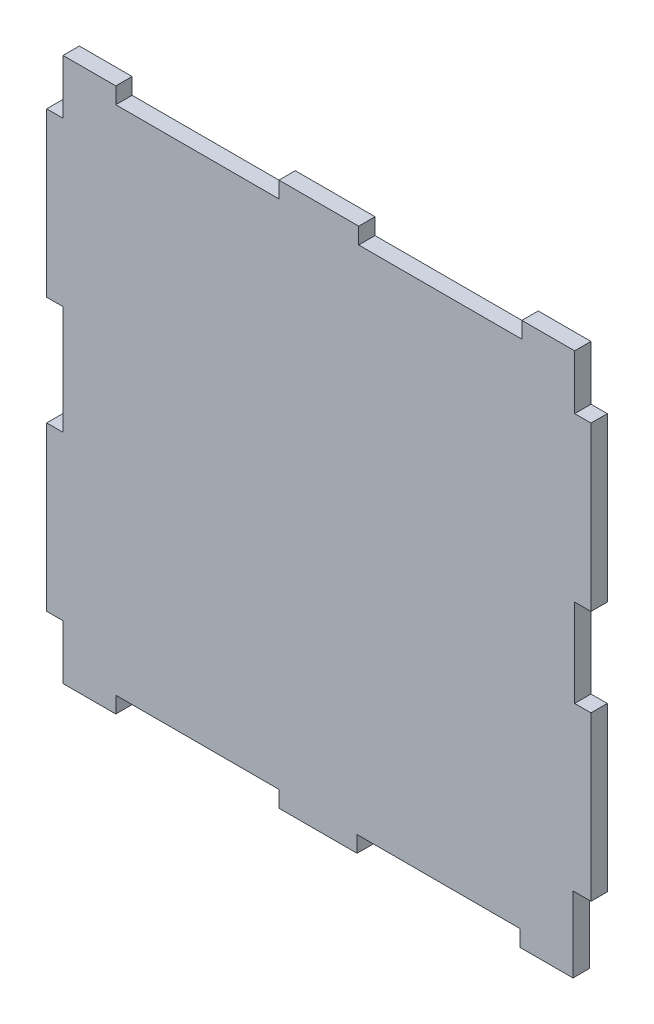
SolidWorks part; units mm, degrees
ref_plane "Plan de face" through (0, 0, 0) normal (0, 0, 1) x (1, 0, 0)
ref_plane "Plan de dessus" through (0, 0, 0) normal (0, 1, 0) x (1, 0, 0)
ref_plane "Plan de droite" through (0, 0, 0) normal (1, 0, 0) x (0, 0, -1)
sketch "Esquisse1" plane through (0, 0, 0) normal (0, 0, 1) x (1, 0, 0)
  line L0 (-57.5181, -33.4139) -> (-57.5181, -63.4139)
  line L1 (-54.5181, 26.5861) -> (-44.8181, 26.5861)
  line L2 (-57.5181, 16.5861) -> (-57.5181, -13.4139)
  line L3 (-54.5181, -73.4139) -> (-44.8181, -73.4139)
  line L4 (42.535, 16.5861) -> (42.535, -13.4139)
  line L7 (42.535, 16.5861) -> (39.535, 16.5861)
  line L8 (39.535, 26.5861) -> (39.535, 16.5861)
  line L9 (-14.8181, 26.5861) -> (-0.165, 26.5861)
  line L10 (42.535, -59.551) -> (39.2275, -59.551)
  line L11 (39.2275, -73.4139) -> (39.2275, -59.551)
  line L12 (42.535, -13.4139) -> (39.535, -13.4139)
  line L13 (29.835, 26.5861) -> (39.535, 26.5861)
  line L14 (42.535, -29.551) -> (39.535, -29.551)
  line L15 (39.535, -13.4139) -> (39.535, -29.551)
  line L17 (42.535, -29.551) -> (42.535, -59.551)
  line L18 (-57.5181, 16.5861) -> (-54.5181, 16.5861)
  line L19 (-54.5181, 26.5861) -> (-54.5181, 16.5861)
  line L21 (-44.8181, 26.5861) -> (-44.8181, 23.5861)
  line L22 (-57.5181, -63.4139) -> (-54.5181, -63.4139)
  line L23 (-54.5181, -73.4139) -> (-54.5181, -63.4139)
  line L24 (-54.5181, -13.4139) -> (-57.5181, -13.4139)
  line L25 (-54.5181, -13.4139) -> (-54.5181, -33.4139)
  line L26 (-54.5181, -33.4139) -> (-57.5181, -33.4139)
  line L27 (-44.8181, 23.5861) -> (-14.8181, 23.5861)
  line L28 (-14.8181, 26.5861) -> (-14.8181, 23.5861)
  line L29 (-14.8181, -73.4139) -> (-0.4725, -73.4139)
  line L30 (-0.165, 26.5861) -> (-0.165, 23.5861)
  line L31 (-0.165, 23.5861) -> (29.835, 23.5861)
  line L32 (29.835, 26.5861) -> (29.835, 23.5861)
  line L33 (29.5275, -73.4139) -> (39.2275, -73.4139)
  line L34 (-44.8181, -73.4139) -> (-44.8181, -70.4139)
  line L35 (-44.8181, -70.4139) -> (-14.8181, -70.4139)
  line L36 (-14.8181, -73.4139) -> (-14.8181, -70.4139)
  line L38 (-0.4725, -73.4139) -> (-0.4725, -70.4139)
  line L39 (-0.4725, -70.4139) -> (29.5275, -70.4139)
  line L40 (29.5275, -73.4139) -> (29.5275, -70.4139)
  dimension "D3" = 3
  dimension "D4" = 10
  dimension "D5" = 30
  dimension "D6" = 30
  dimension "D7" = 3
  dimension "D8" = 3
  dimension "D9" = 3
  dimension "D10" = 3
  dimension "D11" = 10
  dimension "D12" = 3
  dimension "D13" = 10
  dimension "D14" = 30
  dimension "D15" = 30
  dimension "D16" = 3
  dimension "D17" = 3
  dimension "D18" = 3
  dimension "D19" = 30
  dimension "D20" = 30
  dimension "D21" = 30
  dimension "D22" = 30
  dimension "D23" = 9.7
  dimension "D24" = 9.7
  dimension "D25" = 9.7
  dimension "D26" = 9.7
extrude "Boss.-Extru.1" add sketch "Esquisse1" along normal blind 3
